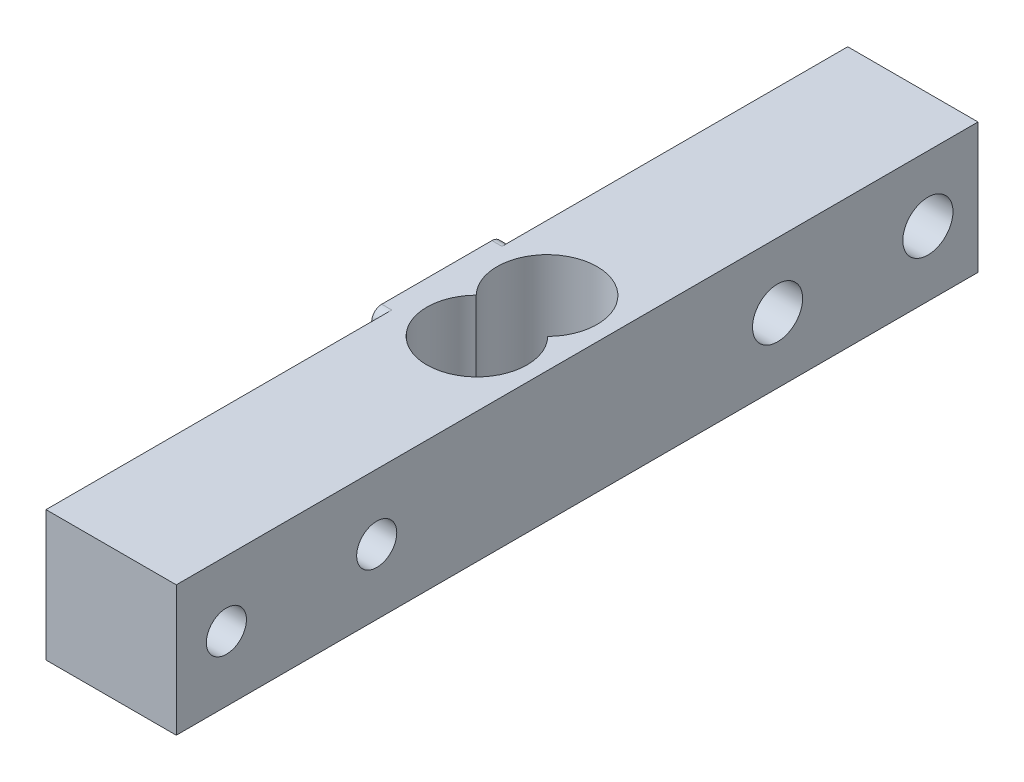
SolidWorks part; units mm, degrees
material "1060 Alloy"
ref_plane "Front Plane" through (0, 0, 0) normal (0, 0, 1) x (1, 0, 0)
ref_plane "Top Plane" through (0, 0, 0) normal (0, 1, 0) x (1, 0, 0)
ref_plane "Right Plane" through (0, 0, 0) normal (1, 0, 0) x (0, 0, -1)
sketch "Sketch1" plane through (0, 0, 0) normal (0, 0, 1) x (1, 0, 0)
  line L1 (-6.5, 6.5) -> (6.5, 6.5)
  line L2 (-6.5, 6.5) -> (-6.5, -6.5)
  line L3 (-6.5, -6.5) -> (6.5, -6.5)
  line L4 (6.5, 6.5) -> (6.5, -6.5)
  line L5 (-6.5, 6.5) -> (6.5, -6.5) construction
  line L6 (-6.5, -6.5) -> (6.5, 6.5) construction
  point P0 (0, 0)
  dimension "D1" = 13
extrude "Boss-Extrude1" add sketch "Sketch1" along normal mid plane 80
sketch "Sketch2" plane through (0, 6.5, 0) normal (0, 1, 0) x (1, 0, 0)
  line L0 (0, -3.5) -> (0, 3.5) construction
  arc A0 (3.5707, 0) -> (-3.5707, 0) centre (0, 3.5) ccw
  arc A1 (-3.5707, 0) -> (3.5707, 0) centre (0, -3.5) ccw
  dimension "D2" = 10
  dimension "D3" = 10
  dimension "D1" = 7
extrude "Cut-Extrude1" cut sketch "Sketch2" against normal through all
sketch "Sketch3" plane through (6.5, 0, 0) normal (1, 0, 0) x (0, 0, -1)
  line L0 (-40, 0) -> (40, 0) construction
  line L1 (-40, -6.5) -> (-40, 6.5) construction
  line L2 (40, -6.5) -> (40, 6.5) construction
  circle A0 centre (-35, 0) radius 2
  circle A1 centre (-20, 0) radius 2
  circle A2 centre (20, 0) radius 2.5
  circle A3 centre (35, 0) radius 2.5
  dimension "D1" = 4
  dimension "D2" = 4
  dimension "D3" = 5
  dimension "D4" = 5
  dimension "D5" = 15
  dimension "D6" = 5
  dimension "D7" = 15
  dimension "D8" = 5
extrude "Cut-Extrude2" cut sketch "Sketch3" against normal through all
sketch "Sketch5" plane through (-6.5, 0, 0) normal (-1, 0, 0) x (0, 0, 1)
  line L0 (40, -6.5) -> (-40, -6.5) construction
  line L1 (-6.5, 6.5) -> (6.5, 6.5)
  line L2 (-6.5, 6.5) -> (-6.5, -6.5)
  line L3 (-6.5, -6.5) -> (6.5, -6.5)
  line L4 (6.5, 6.5) -> (6.5, -6.5)
  line L5 (-6.5, 6.5) -> (6.5, -6.5) construction
  line L6 (-6.5, -6.5) -> (6.5, 6.5) construction
  point P0 (0, 0)
  dimension "D1" = 13
extrude "Boss-Extrude2" add sketch "Sketch5" along normal blind 1
fillet "Fillet1" radius 1 4 edges at (-7, -6.5, 6.5) (-7, 6.5, 6.5) (-7, 6.5, -6.5) (-7, -6.5, -6.5)
